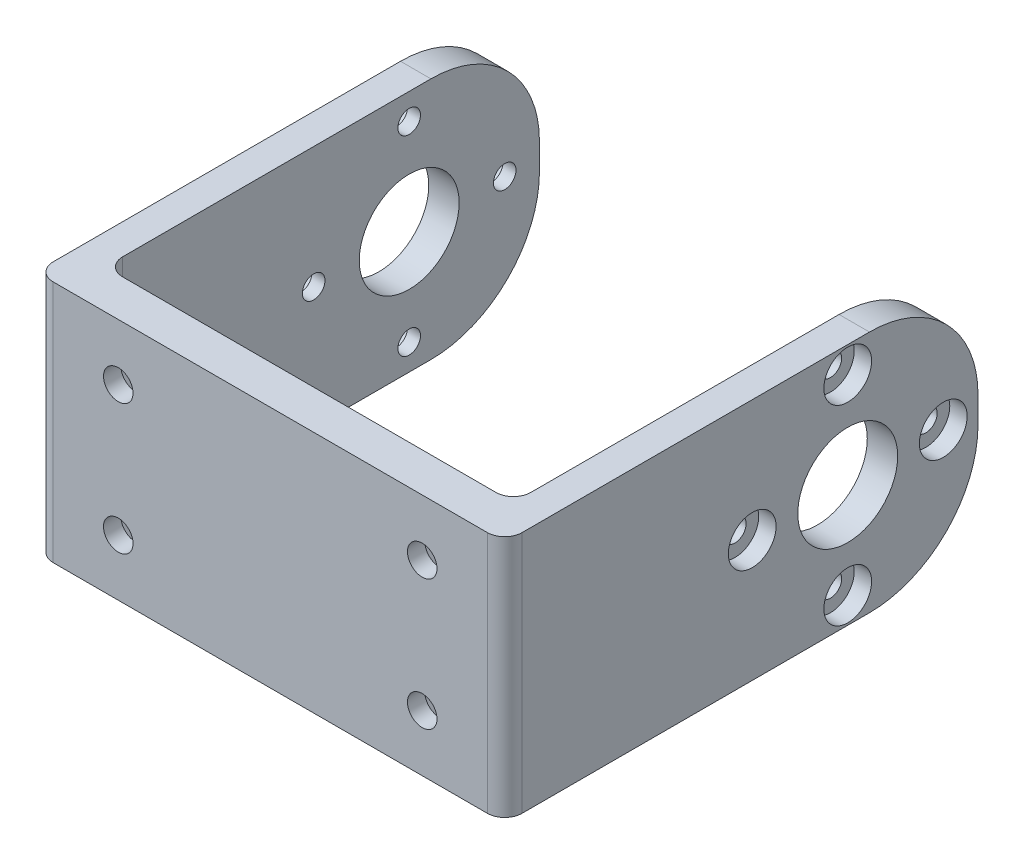
SolidWorks part; units mm, degrees
ref_plane "Front Plane" through (0, 0, 0) normal (0, 0, 1) x (1, 0, 0)
ref_plane "Top Plane" through (0, 0, 0) normal (0, 1, 0) x (1, 0, 0)
ref_plane "Right Plane" through (0, 0, 0) normal (1, 0, 0) x (0, 0, -1)
sketch "Sketch1" plane through (0, 0, 0) normal (0, 1, 0) x (1, 0, 0)
  line L0 (-27, 50) -> (-27, -4.5)
  line L1 (-27, -4.5) -> (27, -4.5)
  line L2 (27, -4.5) -> (27, 50)
  line L3 (27, 50) -> (23.5, 50)
  line L4 (23.5, 50) -> (23.5, 0)
  line L5 (23.5, 0) -> (-23.5, 0)
  line L6 (-23.5, 0) -> (-23.5, 50)
  line L7 (-23.5, 50) -> (-27, 50)
  point P3 (0, 0)
  dimension "D1" = 47
  dimension "D2" = 3.5
  dimension "D3" = 4.5
  dimension "D4" = 50
extrude "Boss-Extrude1" add sketch "Sketch1" along normal blind 28
sketch "Sketch3" plane through (27, 0, 0) normal (1, 0, 0) x (0, 0, -1)
  line L0 (-4.5, 28) -> (-4.5, 0) construction
  line L1 (50, 28) -> (50, 0) construction
  circle A0 centre (35, 14) radius 5.75
  circle A1 centre (46, 14) radius 1.3
  circle A2 centre (35, 3) radius 1.3
  circle A3 centre (24, 14) radius 1.3
  circle A4 centre (35, 25) radius 1.3
  point P5 (-4.5, 14)
  point P16 (35, 14)
  dimension "D1" = 11.5
  dimension "D2" = 2.6
  dimension "D4" = 15
  dimension "D5" = 11
  dimension "D3" = 4
extrude "Cut-Extrude1" cut sketch "Sketch3" against normal through all
sketch "Sketch4" plane through (0, 0, 4.5) normal (0, 0, 1) x (1, 0, 0)
  line L0 (-27, 28) -> (-27, 0) construction
  line L1 (-17.5, 21.5) -> (17.5, 21.5) construction
  line L2 (-17.5, 21.5) -> (-17.5, 6.5) construction
  line L3 (-17.5, 6.5) -> (17.5, 6.5) construction
  line L4 (17.5, 21.5) -> (17.5, 6.5) construction
  line L5 (0, 6.5) -> (0, 21.5) construction
  line L6 (-17.5, 14) -> (17.5, 14) construction
  circle A0 centre (-17.5, 6.5) radius 1.7
  circle A1 centre (17.5, 6.5) radius 1.7
  circle A2 centre (17.5, 21.5) radius 1.7
  circle A3 centre (-17.5, 21.5) radius 1.7
  point P14 (-27, 14)
  point P226 (0, 14)
  dimension "D1" = 3.4
  dimension "D4" = 15
  dimension "D5" = 35
  dimension "D2" = 2
  dimension "D3" = 2
extrude "Cut-Extrude2" cut sketch "Sketch4" against normal blind 25
fillet "Fillet1" radius 2 4 edges at (23.5, 14, 0) (27, 14, 4.5) (-27, 14, 4.5) (-23.5, 14, 0)
fillet "Fillet2" radius 12.5 4 edges at (-25.25, 0, -50) (-25.25, 28, -50) (25.25, 28, -50) (25.25, 0, -50)
sketch "Sketch5" plane through (0, 0, 0) normal (0, 0, -1) x (-1, 0, 0)
  line L0 (19.1743, 18.6) -> (20.8486, 21.5)
  line L1 (-15.8257, 18.6) -> (-14.1514, 21.5)
  line L2 (-14.1514, 21.5) -> (-15.8257, 24.4)
  line L3 (-15.8257, 24.4) -> (-19.1743, 24.4)
  line L4 (-19.1743, 24.4) -> (-20.8486, 21.5)
  line L5 (-20.8486, 21.5) -> (-19.1743, 18.6)
  line L6 (-19.1743, 18.6) -> (-15.8257, 18.6)
  line L7 (20.8486, 21.5) -> (19.1743, 24.4)
  line L8 (19.1743, 24.4) -> (15.8257, 24.4)
  line L9 (15.8257, 24.4) -> (14.1514, 21.5)
  line L10 (14.1514, 21.5) -> (15.8257, 18.6)
  line L11 (15.8257, 18.6) -> (19.1743, 18.6)
  line L12 (19.1743, 3.6) -> (20.8486, 6.5)
  line L13 (20.8486, 6.5) -> (19.1743, 9.4)
  line L14 (19.1743, 9.4) -> (15.8257, 9.4)
  line L15 (15.8257, 9.4) -> (14.1514, 6.5)
  line L16 (14.1514, 6.5) -> (15.8257, 3.6)
  line L17 (15.8257, 3.6) -> (19.1743, 3.6)
  line L18 (-15.8257, 3.6) -> (-14.1514, 6.5)
  line L19 (-14.1514, 6.5) -> (-15.8257, 9.4)
  line L20 (-15.8257, 9.4) -> (-19.1743, 9.4)
  line L21 (-19.1743, 9.4) -> (-20.8486, 6.5)
  line L22 (-20.8486, 6.5) -> (-19.1743, 3.6)
  line L23 (-19.1743, 3.6) -> (-15.8257, 3.6)
  circle A0 centre (-17.5, 21.5) radius 2.9 construction
  circle A1 centre (17.5, 21.5) radius 2.9 construction
  circle A2 centre (17.5, 6.5) radius 2.9 construction
  circle A3 centre (-17.5, 6.5) radius 2.9 construction
  dimension "D1" = 5.8
  dimension "D2" = 2
  dimension "D3" = 2
extrude "Cut-Extrude3" cut sketch "Sketch5" against normal blind 2.5
sketch "Sketch6" plane through (27, 0, 0) normal (1, 0, 0) x (0, 0, -1)
  circle A0 centre (24, 14) radius 2.75
  circle A1 centre (35, 25) radius 2.75
  circle A2 centre (46, 14) radius 2.75
  circle A3 centre (35, 3) radius 2.75
  point P12 (35, 14)
  dimension "D1" = 5.5
  dimension "D2" = 4
extrude "Cut-Extrude4" cut sketch "Sketch6" against normal blind 2
sketch "Sketch9" plane through (-27, 0, 0) normal (-1, 0, 0) x (0, 0, 1)
  circle A0 centre (-46, 14) radius 2.75
  circle A1 centre (-35, 25) radius 2.75
  circle A2 centre (-24, 14) radius 2.75
  circle A3 centre (-35, 3) radius 2.75
  point P12 (-35, 14)
  dimension "D1" = 5.5
  dimension "D2" = 4
extrude "Cut-Extrude5" cut sketch "Sketch9" against normal blind 2
